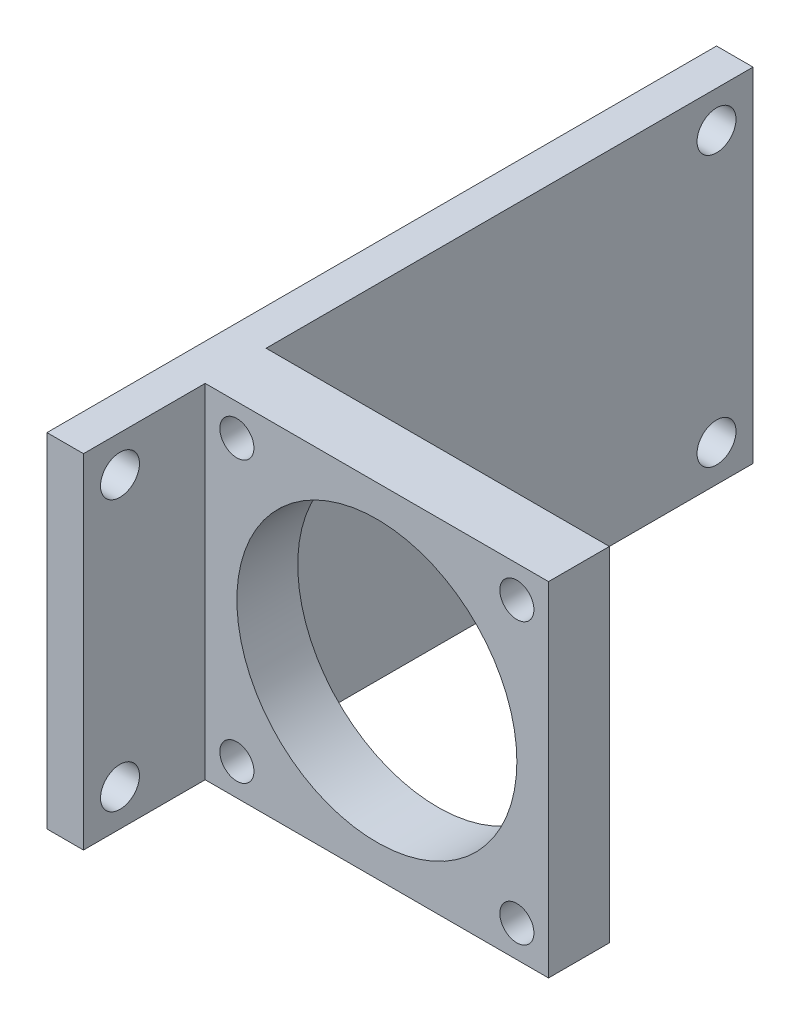
SolidWorks part; units mm, degrees
ref_plane "Front Plane" through (0, 0, 0) normal (0, 0, 1) x (1, 0, 0)
ref_plane "Top Plane" through (0, 0, 0) normal (0, 1, 0) x (1, 0, 0)
ref_plane "Right Plane" through (0, 0, 0) normal (1, 0, 0) x (0, 0, -1)
sketch "Sketch2" plane through (0, 0, 0) normal (0, 0, 1) x (1, 0, 0)
  line L1 (3.2174, 58.6168) -> (31.4174, 58.6168)
  line L2 (3.2174, 58.6168) -> (3.2174, 30.4168)
  line L3 (3.2174, 30.4168) -> (31.4174, 30.4168)
  line L4 (31.4174, 58.6168) -> (31.4174, 30.4168)
  dimension "D1" = 28.2
  dimension "D2" = 28.2
extrude "Boss-Extrude1" add sketch "Sketch2" along normal blind 5
sketch "Sketch3" plane through (0, 0, 5) normal (0, 0, 1) x (1, 0, 0)
  line L0 (31.4174, 58.6168) -> (3.2174, 58.6168) construction
  line L1 (3.2174, 58.6168) -> (3.2174, 30.4168) construction
  line L2 (31.4174, 30.4168) -> (31.4174, 58.6168) construction
  line L3 (3.2174, 30.4168) -> (31.4174, 30.4168) construction
  circle A0 centre (5.8174, 56.0168) radius 1.4
  circle A1 centre (28.8174, 56.0168) radius 1.4
  circle A2 centre (28.8174, 33.0168) radius 1.4
  circle A3 centre (5.8174, 33.0168) radius 1.4
  dimension "D1" = 2.8
  dimension "D2" = 2.8
  dimension "D3" = 2.8
  dimension "D4" = 2.8
  dimension "D5" = 2.6
  dimension "D6" = 2.6
  dimension "D7" = 2.6
  dimension "D8" = 2.6
  dimension "D9" = 2.6
  dimension "D10" = 2.6
  dimension "D11" = 2.6
  dimension "D12" = 2.6
extrude "Cut-Extrude1" cut sketch "Sketch3" against normal blind 5
sketch "Sketch4" plane through (0, 0, 5) normal (0, 0, 1) x (1, 0, 0)
  line L0 (31.4174, 58.6168) -> (3.2174, 58.6168) construction
  line L1 (3.2174, 58.6168) -> (3.2174, 30.4168) construction
  circle A0 centre (17.3174, 44.5168) radius 11.5
  dimension "D1" = 23
  dimension "D2" = 14.1
  dimension "D3" = 14.1
extrude "Cut-Extrude2" cut sketch "Sketch4" against normal blind 5
sketch "Sketch7" plane through (3.2174, 0, 0) normal (-1, 0, 0) x (0, 0, 1)
  line L0 (5, 58.6168) -> (5, 30.4168) construction
  line L1 (15, 58.6168) -> (-40, 58.6168)
  line L2 (15, 58.6168) -> (15, 30.4168)
  line L3 (15, 30.4168) -> (-40, 30.4168)
  line L4 (-40, 58.6168) -> (-40, 30.4168)
  line L5 (0, 58.6168) -> (0, 30.4168) construction
  line L6 (5, 30.4168) -> (0, 30.4168) construction
  dimension "D1" = 10
  dimension "D2" = 40
  dimension "D3" = 28.2
  dimension "D4" = 0
extrude "Boss-Extrude2" add sketch "Sketch7" along normal blind 3
sketch "Sketch10" plane through (3.2174, 0, 0) normal (1, 0, 0) x (0, 0, -1)
  line L0 (40, 58.6168) -> (40, 30.4168) construction
  line L1 (40, 30.4168) -> (0, 30.4168) construction
  line L2 (0, 58.6168) -> (40, 58.6168) construction
  line L3 (-15, 58.6168) -> (-5, 58.6168) construction
  line L4 (-15, 30.4168) -> (-15, 58.6168) construction
  line L5 (-5, 30.4168) -> (-15, 30.4168) construction
  circle A0 centre (37, 55.6168) radius 1.6
  circle A1 centre (37, 33.4168) radius 1.6
  circle A2 centre (-12, 55.6168) radius 1.6
  circle A3 centre (-12, 33.4168) radius 1.6
  dimension "D1" = 3.2
  dimension "D2" = 3.2
  dimension "D3" = 3.2
  dimension "D4" = 3.2
  dimension "D5" = 3
  dimension "D6" = 3
  dimension "D7" = 3
  dimension "D8" = 3
  dimension "D9" = 3
  dimension "D10" = 3
  dimension "D11" = 3
  dimension "D12" = 3
extrude "Cut-Extrude7" cut sketch "Sketch10" against normal blind 5
